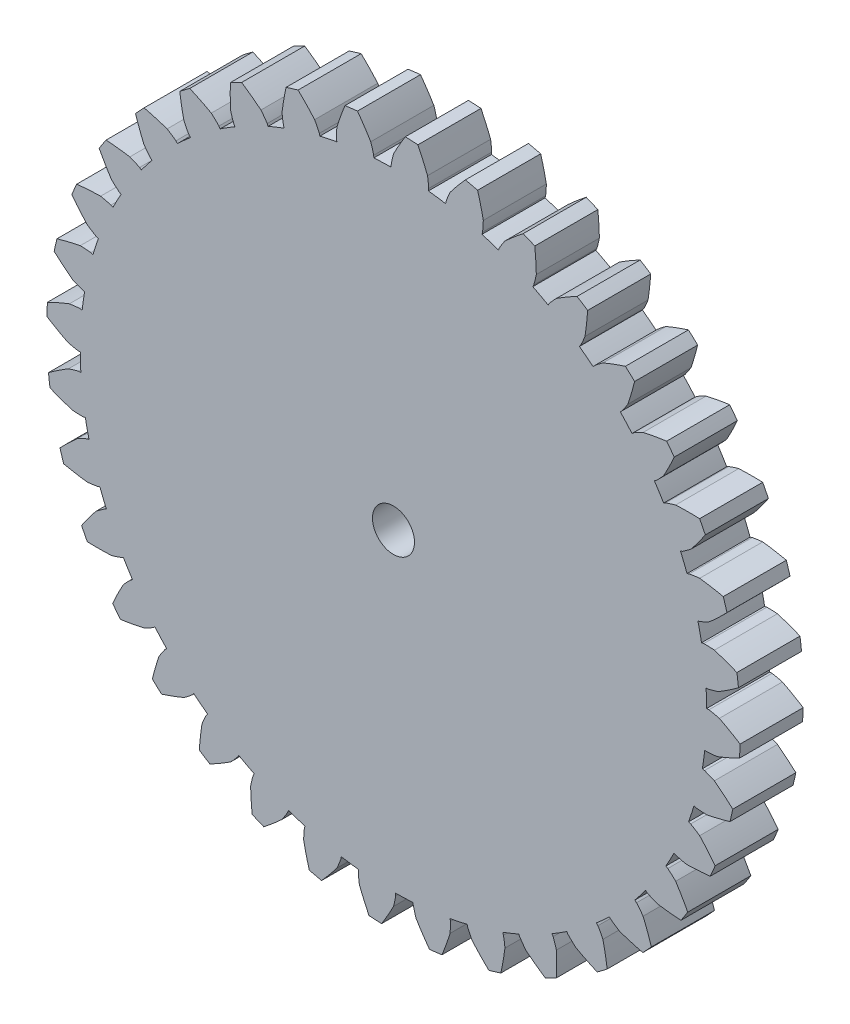
SolidWorks part; units mm, degrees
ref_plane "Front Plane" through (0, 0, 0) normal (0, 0, 1) x (1, 0, 0)
ref_plane "Top Plane" through (0, 0, 0) normal (0, 1, 0) x (1, 0, 0)
ref_plane "Right Plane" through (0, 0, 0) normal (1, 0, 0) x (0, 0, -1)
sketch "Sketch1" plane through (0, 0, 0) normal (0, 0, 1) x (1, 0, 0)
  line L0 (0, 5.8931) -> (0, -6.7835) construction
  line L1 (-10.3696, 0) -> (9.5981, 0) construction
  line L2 (-7.5145, 29.0566) -> (0, 0) construction
  line L3 (0, 0) -> (1.707, -6.6006) construction
  line L4 (-3.7573, 14.5283) -> (0, 15.5) construction
  line L5 (0, 15.5) -> (1.6202, 15.4151) construction
  line L6 (0, 0) -> (0.8101, 15.4575) construction
  line L7 (-0.1058, 15.0059) -> (-0.1058, 14.8996)
  line L8 (1.6737, 14.9127) -> (1.6626, 14.8069)
  line L9 (2.5016, 14.7963) -> (2.4831, 14.6916)
  line L10 (4.2379, 14.3955) -> (4.2086, 14.2933)
  line L11 (5.0329, 14.1371) -> (4.9966, 14.0372)
  line L12 (6.6732, 13.4409) -> (6.6266, 13.3453)
  line L13 (7.4114, 13.0484) -> (7.3582, 12.9563)
  line L14 (8.9058, 12.0779) -> (8.8433, 11.9919)
  line L15 (9.5646, 11.5632) -> (9.4963, 11.4818)
  line L16 (10.8678, 10.3479) -> (10.7914, 10.2741)
  line L17 (11.4272, 9.7266) -> (11.3458, 9.6583)
  line L18 (12.4996, 8.3035) -> (12.4115, 8.2441)
  line L19 (12.9426, 7.5946) -> (12.8506, 7.5414)
  line L20 (13.7516, 6.0068) -> (13.6545, 5.9636)
  line L21 (14.0648, 5.2317) -> (13.9649, 5.1954)
  line L22 (14.5858, 3.5276) -> (14.4826, 3.5019)
  line L23 (14.7596, 2.7099) -> (14.6549, 2.6915)
  line L24 (14.9767, 0.9413) -> (14.8707, 0.9338)
  line L25 (15.0059, 0.1058) -> (14.8996, 0.1058)
  line L26 (14.9127, -1.6737) -> (14.8069, -1.6626)
  line L27 (14.7963, -2.5016) -> (14.6916, -2.4831)
  line L28 (14.3955, -4.2379) -> (14.2933, -4.2086)
  line L29 (14.1371, -5.0329) -> (14.0372, -4.9966)
  line L30 (13.4409, -6.6732) -> (13.3453, -6.6266)
  line L31 (13.0484, -7.4114) -> (12.9563, -7.3582)
  line L32 (12.0779, -8.9058) -> (11.9919, -8.8433)
  line L33 (11.5632, -9.5646) -> (11.4818, -9.4963)
  line L34 (10.3479, -10.8678) -> (10.2741, -10.7914)
  line L35 (9.7266, -11.4272) -> (9.6583, -11.3458)
  line L36 (8.3035, -12.4996) -> (8.2441, -12.4115)
  line L37 (7.5946, -12.9426) -> (7.5414, -12.8506)
  line L38 (6.0068, -13.7516) -> (5.9636, -13.6545)
  line L39 (5.2317, -14.0648) -> (5.1954, -13.9649)
  line L40 (3.5276, -14.5858) -> (3.5019, -14.4826)
  line L41 (2.7099, -14.7596) -> (2.6915, -14.6549)
  line L42 (0.9413, -14.9767) -> (0.9338, -14.8707)
  line L43 (0.1058, -15.0059) -> (0.1058, -14.8996)
  line L44 (-1.6737, -14.9127) -> (-1.6626, -14.8069)
  line L45 (-2.5016, -14.7963) -> (-2.4831, -14.6916)
  line L46 (-4.2379, -14.3955) -> (-4.2086, -14.2933)
  line L47 (-5.0329, -14.1371) -> (-4.9966, -14.0372)
  line L48 (-6.6732, -13.4409) -> (-6.6266, -13.3453)
  line L49 (-7.4114, -13.0484) -> (-7.3582, -12.9563)
  line L50 (-8.9058, -12.0779) -> (-8.8433, -11.9919)
  line L51 (-9.5646, -11.5632) -> (-9.4963, -11.4818)
  line L52 (-10.8678, -10.3479) -> (-10.7914, -10.2741)
  line L53 (-11.4272, -9.7266) -> (-11.3458, -9.6583)
  line L54 (-12.4996, -8.3035) -> (-12.4115, -8.2441)
  line L55 (-12.9426, -7.5946) -> (-12.8506, -7.5414)
  line L56 (-13.7516, -6.0068) -> (-13.6545, -5.9636)
  line L57 (-14.0648, -5.2317) -> (-13.9649, -5.1954)
  line L58 (-14.5858, -3.5276) -> (-14.4826, -3.5019)
  line L59 (-14.7596, -2.7099) -> (-14.6549, -2.6915)
  line L60 (-14.9767, -0.9413) -> (-14.8707, -0.9338)
  line L61 (-15.0059, -0.1058) -> (-14.8996, -0.1058)
  line L62 (-14.9127, 1.6737) -> (-14.8069, 1.6626)
  line L63 (-14.7963, 2.5016) -> (-14.6916, 2.4831)
  line L64 (-14.3955, 4.2379) -> (-14.2933, 4.2086)
  line L65 (-14.1371, 5.0329) -> (-14.0372, 4.9966)
  line L66 (-13.4409, 6.6732) -> (-13.3453, 6.6266)
  line L67 (-13.0484, 7.4114) -> (-12.9563, 7.3582)
  line L68 (-12.0779, 8.9058) -> (-11.9919, 8.8433)
  line L69 (-11.5632, 9.5646) -> (-11.4818, 9.4963)
  line L70 (-10.3479, 10.8678) -> (-10.2741, 10.7914)
  line L71 (-9.7266, 11.4272) -> (-9.6583, 11.3458)
  line L72 (-8.3035, 12.4996) -> (-8.2441, 12.4115)
  line L73 (-7.5946, 12.9426) -> (-7.5414, 12.8506)
  line L74 (-6.0068, 13.7516) -> (-5.9636, 13.6545)
  line L75 (-5.2317, 14.0648) -> (-5.1954, 13.9649)
  line L76 (-3.5276, 14.5858) -> (-3.5019, 14.4826)
  line L77 (-2.7099, 14.7596) -> (-2.6915, 14.6549)
  line L78 (-0.9413, 14.9767) -> (-0.9338, 14.8707)
  circle A0 centre (0, 0) radius 15.5 construction
  arc A1 (-0.1058, 14.8996) -> (-0.9338, 14.8707) centre (0, 0) ccw
  arc A2 (1.1622, 16.459) -> (0.5646, 16.4903) centre (0, 0) ccw
  circle A3 centre (0, 0) radius 15.0063 construction
  arc A4 (0, 15.5) -> (0.5646, 16.4903) centre (11.5649, 9.5625) cw
  arc A5 (0, 15.5) -> (-0.1058, 15.0059) centre (4.8301, 14.2077) ccw
  arc A6 (1.6202, 15.4151) -> (1.1622, 16.459) centre (-10.502, 10.719) ccw
  arc A7 (1.6202, 15.4151) -> (1.6737, 14.9127) centre (-3.3185, 14.6348) cw
  arc A8 (0, 16.5) -> (16.5, 0) centre (0, 0) ccw construction
  arc A9 (2.6915, 15.2645) -> (2.5016, 14.7963) centre (7.2239, 13.1531) ccw
  arc A10 (2.6915, 15.2645) -> (3.4196, 16.1418) centre (13.0497, 7.409) cw
  arc A11 (4.0026, 16.0072) -> (3.4196, 16.1418) centre (0, 0) ccw
  arc A12 (4.2724, 14.8996) -> (4.0026, 16.0072) centre (-8.4811, 12.3798) ccw
  arc A13 (4.2724, 14.8996) -> (4.2379, 14.3955) centre (-0.7268, 14.9887) cw
  arc A14 (5.3013, 14.5652) -> (5.0329, 14.1371) centre (9.3981, 11.6989) ccw
  arc A15 (5.3013, 14.5652) -> (6.1706, 15.3027) centre (14.138, 5.0304) cw
  arc A16 (6.7214, 15.0689) -> (6.1706, 15.3027) centre (0, 0) ccw
  arc A17 (6.7948, 13.9313) -> (6.7214, 15.0689) centre (-6.2025, 13.6645) ccw
  arc A18 (6.7948, 13.9313) -> (6.6732, 13.4409) centre (1.887, 14.8872) cw
  arc A19 (7.75, 13.4234) -> (7.4114, 13.0484) centre (11.2868, 9.8892) ccw
  arc A20 (7.75, 13.4234) -> (8.7342, 13.9987) centre (14.7968, 2.499) cw
  arc A21 (9.236, 13.6728) -> (8.7342, 13.9987) centre (0, 0) ccw
  arc A22 (9.1107, 12.5398) -> (9.236, 13.6728) centre (-3.7355, 14.5339) ccw
  arc A23 (9.1107, 12.5398) -> (8.9058, 12.0779) centre (4.4434, 14.3333) cw
  arc A24 (9.9632, 11.8737) -> (9.5646, 11.5632) centre (12.8326, 7.779) ccw
  arc A25 (9.9632, 11.8737) -> (11.0323, 12.2694) centre (15.0059, -0.1084) cw
  arc A26 (11.4699, 11.8613) -> (11.0323, 12.2694) centre (0, 0) ccw
  arc A27 (11.1498, 10.7672) -> (11.4699, 11.8613) centre (-1.1549, 14.9618) ccw
  arc A28 (11.1498, 10.7672) -> (10.8678, 10.3479) centre (6.8649, 13.344) cw
  arc A29 (11.8737, 9.9632) -> (11.4272, 9.7266) centre (13.9885, 5.4325) ccw
  arc A30 (11.8737, 9.9632) -> (12.9953, 10.1673) centre (14.7591, -2.7125) cw
  arc A31 (13.3554, 9.6894) -> (12.9953, 10.1673) centre (0, 0) ccw
  arc A32 (12.8501, 8.6675) -> (13.3554, 9.6894) centre (1.4607, 14.935) ccw
  arc A33 (12.8501, 8.6675) -> (12.4996, 8.3035) centre (9.0778, 11.9492) cw
  arc A34 (13.4234, 7.75) -> (12.9426, 7.5946) centre (14.7193, 2.9209) ccw
  arc A35 (13.4234, 7.75) -> (14.5634, 7.7562) centre (14.0638, -5.2342) cw
  arc A36 (14.835, 7.223) -> (14.5634, 7.7562) centre (0, 0) ccw
  arc A37 (14.16, 6.3044) -> (14.835, 7.223) centre (4.032, 14.4545) ccw
  arc A38 (14.16, 6.3044) -> (13.7516, 6.0068) centre (11.0148, 10.1913) cw
  arc A39 (14.5652, 5.3013) -> (14.0648, 5.2317) centre (15.0029, 0.3205) ccw
  arc A40 (14.5652, 5.3013) -> (15.689, 5.1094) centre (12.9413, -7.5969) cw
  arc A41 (15.8639, 4.5372) -> (15.689, 5.1094) centre (0, 0) ccw
  arc A42 (15.0396, 3.7498) -> (15.8639, 4.5372) centre (6.4807, 13.5347) ccw
  arc A43 (15.0396, 3.7498) -> (14.5858, 3.5276) centre (12.6172, 8.1238) cw
  arc A44 (15.2645, 2.6915) -> (14.7596, 2.7099) centre (14.8306, -2.2896) ccw
  arc A45 (15.2645, 2.6915) -> (16.3379, 2.3075) centre (11.4255, -9.7287) cw
  arc A46 (16.4108, 1.7136) -> (16.3379, 2.3075) centre (0, 0) ccw
  arc A47 (15.4622, 1.0812) -> (16.4108, 1.7136) centre (8.7325, 12.2038) ccw
  arc A48 (15.4622, 1.0812) -> (14.9767, 0.9413) centre (13.8362, 5.8094) cw
  arc A49 (15.5, 0) -> (15.0059, 0.1058) centre (14.2077, -4.8301) ccw
  arc A50 (15.5, 0) -> (16.4903, -0.5646) centre (9.5625, -11.5649) cw
  arc A51 (16.459, -1.1622) -> (16.4903, -0.5646) centre (0, 0) ccw
  arc A52 (15.4151, -1.6202) -> (16.459, -1.1622) centre (10.719, 10.502) ccw
  arc A53 (15.4151, -1.6202) -> (14.9127, -1.6737) centre (14.6348, 3.3185) cw
  arc A54 (15.2645, -2.6915) -> (14.7963, -2.5016) centre (13.1531, -7.2239) ccw
  arc A55 (15.2645, -2.6915) -> (16.1418, -3.4196) centre (7.409, -13.0497) cw
  arc A56 (16.0072, -4.0026) -> (16.1418, -3.4196) centre (0, 0) ccw
  arc A57 (14.8996, -4.2724) -> (16.0072, -4.0026) centre (12.3798, 8.4811) ccw
  arc A58 (14.8996, -4.2724) -> (14.3955, -4.2379) centre (14.9887, 0.7268) cw
  arc A59 (14.5652, -5.3013) -> (14.1371, -5.0329) centre (11.6989, -9.3981) ccw
  arc A60 (14.5652, -5.3013) -> (15.3027, -6.1706) centre (5.0304, -14.138) cw
  arc A61 (15.0689, -6.7214) -> (15.3027, -6.1706) centre (0, 0) ccw
  arc A62 (13.9313, -6.7948) -> (15.0689, -6.7214) centre (13.6645, 6.2025) ccw
  arc A63 (13.9313, -6.7948) -> (13.4409, -6.6732) centre (14.8872, -1.887) cw
  arc A64 (14.0372, -4.9966) -> (14.2933, -4.2086) centre (0, 0) ccw
  arc A65 (14.6916, -2.4831) -> (14.8069, -1.6626) centre (0, 0) ccw
  arc A66 (14.8996, 0.1058) -> (14.8707, 0.9338) centre (0, 0) ccw
  arc A67 (14.6549, 2.6915) -> (14.4826, 3.5019) centre (0, 0) ccw
  arc A68 (13.9649, 5.1954) -> (13.6545, 5.9636) centre (0, 0) ccw
  arc A69 (12.8506, 7.5414) -> (12.4115, 8.2441) centre (0, 0) ccw
  arc A70 (11.3458, 9.6583) -> (10.7914, 10.2741) centre (0, 0) ccw
  arc A71 (9.4963, 11.4818) -> (8.8433, 11.9919) centre (0, 0) ccw
  arc A72 (7.3582, 12.9563) -> (6.6266, 13.3453) centre (0, 0) ccw
  arc A73 (4.9966, 14.0372) -> (4.2086, 14.2933) centre (0, 0) ccw
  arc A74 (2.4831, 14.6916) -> (1.6626, 14.8069) centre (0, 0) ccw
  circle A75 centre (0, 0) radius 1
  arc A76 (13.4234, -7.75) -> (13.0484, -7.4114) centre (9.8892, -11.2868) ccw
  arc A77 (13.4234, -7.75) -> (13.9987, -8.7342) centre (2.499, -14.7968) cw
  arc A78 (13.6728, -9.236) -> (13.9987, -8.7342) centre (0, 0) ccw
  arc A79 (12.5398, -9.1107) -> (13.6728, -9.236) centre (14.5339, 3.7355) ccw
  arc A80 (12.5398, -9.1107) -> (12.0779, -8.9058) centre (14.3333, -4.4434) cw
  arc A81 (11.8737, -9.9632) -> (11.5632, -9.5646) centre (7.779, -12.8326) ccw
  arc A82 (11.8737, -9.9632) -> (12.2694, -11.0323) centre (-0.1084, -15.0059) cw
  arc A83 (11.8613, -11.4699) -> (12.2694, -11.0323) centre (0, 0) ccw
  arc A84 (10.7672, -11.1498) -> (11.8613, -11.4699) centre (14.9618, 1.1549) ccw
  arc A85 (10.7672, -11.1498) -> (10.3479, -10.8678) centre (13.344, -6.8649) cw
  arc A86 (9.9632, -11.8737) -> (9.7266, -11.4272) centre (5.4325, -13.9885) ccw
  arc A87 (9.9632, -11.8737) -> (10.1673, -12.9953) centre (-2.7125, -14.7591) cw
  arc A88 (9.6894, -13.3554) -> (10.1673, -12.9953) centre (0, 0) ccw
  arc A89 (8.6675, -12.8501) -> (9.6894, -13.3554) centre (14.935, -1.4607) ccw
  arc A90 (8.6675, -12.8501) -> (8.3035, -12.4996) centre (11.9492, -9.0778) cw
  arc A91 (7.75, -13.4234) -> (7.5946, -12.9426) centre (2.9209, -14.7193) ccw
  arc A92 (7.75, -13.4234) -> (7.7562, -14.5634) centre (-5.2342, -14.0638) cw
  arc A93 (7.223, -14.835) -> (7.7562, -14.5634) centre (0, 0) ccw
  arc A94 (6.3044, -14.16) -> (7.223, -14.835) centre (14.4545, -4.032) ccw
  arc A95 (6.3044, -14.16) -> (6.0068, -13.7516) centre (10.1913, -11.0148) cw
  arc A96 (5.3013, -14.5652) -> (5.2317, -14.0648) centre (0.3205, -15.0029) ccw
  arc A97 (5.3013, -14.5652) -> (5.1094, -15.689) centre (-7.5969, -12.9413) cw
  arc A98 (4.5372, -15.8639) -> (5.1094, -15.689) centre (0, 0) ccw
  arc A99 (3.7498, -15.0396) -> (4.5372, -15.8639) centre (13.5347, -6.4807) ccw
  arc A100 (3.7498, -15.0396) -> (3.5276, -14.5858) centre (8.1238, -12.6172) cw
  arc A101 (2.6915, -15.2645) -> (2.7099, -14.7596) centre (-2.2896, -14.8306) ccw
  arc A102 (2.6915, -15.2645) -> (2.3075, -16.3379) centre (-9.7287, -11.4255) cw
  arc A103 (1.7136, -16.4108) -> (2.3075, -16.3379) centre (0, 0) ccw
  arc A104 (1.0812, -15.4622) -> (1.7136, -16.4108) centre (12.2038, -8.7325) ccw
  arc A105 (1.0812, -15.4622) -> (0.9413, -14.9767) centre (5.8094, -13.8362) cw
  arc A106 (0, -15.5) -> (0.1058, -15.0059) centre (-4.8301, -14.2077) ccw
  arc A107 (0, -15.5) -> (-0.5646, -16.4903) centre (-11.5649, -9.5625) cw
  arc A108 (-1.1622, -16.459) -> (-0.5646, -16.4903) centre (0, 0) ccw
  arc A109 (-1.6202, -15.4151) -> (-1.1622, -16.459) centre (10.502, -10.719) ccw
  arc A110 (-1.6202, -15.4151) -> (-1.6737, -14.9127) centre (3.3185, -14.6348) cw
  arc A111 (-2.6915, -15.2645) -> (-2.5016, -14.7963) centre (-7.2239, -13.1531) ccw
  arc A112 (-2.6915, -15.2645) -> (-3.4196, -16.1418) centre (-13.0497, -7.409) cw
  arc A113 (-4.0026, -16.0072) -> (-3.4196, -16.1418) centre (0, 0) ccw
  arc A114 (-4.2724, -14.8996) -> (-4.0026, -16.0072) centre (8.4811, -12.3798) ccw
  arc A115 (-4.2724, -14.8996) -> (-4.2379, -14.3955) centre (0.7268, -14.9887) cw
  arc A116 (-5.3013, -14.5652) -> (-5.0329, -14.1371) centre (-9.3981, -11.6989) ccw
  arc A117 (-5.3013, -14.5652) -> (-6.1706, -15.3027) centre (-14.138, -5.0304) cw
  arc A118 (-6.7214, -15.0689) -> (-6.1706, -15.3027) centre (0, 0) ccw
  arc A119 (-6.7948, -13.9313) -> (-6.7214, -15.0689) centre (6.2025, -13.6645) ccw
  arc A120 (-6.7948, -13.9313) -> (-6.6732, -13.4409) centre (-1.887, -14.8872) cw
  arc A121 (-7.75, -13.4234) -> (-7.4114, -13.0484) centre (-11.2868, -9.8892) ccw
  arc A122 (-7.75, -13.4234) -> (-8.7342, -13.9987) centre (-14.7968, -2.499) cw
  arc A123 (-9.236, -13.6728) -> (-8.7342, -13.9987) centre (0, 0) ccw
  arc A124 (-9.1107, -12.5398) -> (-9.236, -13.6728) centre (3.7355, -14.5339) ccw
  arc A125 (-9.1107, -12.5398) -> (-8.9058, -12.0779) centre (-4.4434, -14.3333) cw
  arc A126 (-9.9632, -11.8737) -> (-9.5646, -11.5632) centre (-12.8326, -7.779) ccw
  arc A127 (-9.9632, -11.8737) -> (-11.0323, -12.2694) centre (-15.0059, 0.1084) cw
  arc A128 (-11.4699, -11.8613) -> (-11.0323, -12.2694) centre (0, 0) ccw
  arc A129 (-11.1498, -10.7672) -> (-11.4699, -11.8613) centre (1.1549, -14.9618) ccw
  arc A130 (-11.1498, -10.7672) -> (-10.8678, -10.3479) centre (-6.8649, -13.344) cw
  arc A131 (-11.8737, -9.9632) -> (-11.4272, -9.7266) centre (-13.9885, -5.4325) ccw
  arc A132 (-11.8737, -9.9632) -> (-12.9953, -10.1673) centre (-14.7591, 2.7125) cw
  arc A133 (-13.3554, -9.6894) -> (-12.9953, -10.1673) centre (0, 0) ccw
  arc A134 (-12.8501, -8.6675) -> (-13.3554, -9.6894) centre (-1.4607, -14.935) ccw
  arc A135 (-12.8501, -8.6675) -> (-12.4996, -8.3035) centre (-9.0778, -11.9492) cw
  arc A136 (-13.4234, -7.75) -> (-12.9426, -7.5946) centre (-14.7193, -2.9209) ccw
  arc A137 (-13.4234, -7.75) -> (-14.5634, -7.7562) centre (-14.0638, 5.2342) cw
  arc A138 (-14.835, -7.223) -> (-14.5634, -7.7562) centre (0, 0) ccw
  arc A139 (-14.16, -6.3044) -> (-14.835, -7.223) centre (-4.032, -14.4545) ccw
  arc A140 (-14.16, -6.3044) -> (-13.7516, -6.0068) centre (-11.0148, -10.1913) cw
  arc A141 (-14.5652, -5.3013) -> (-14.0648, -5.2317) centre (-15.0029, -0.3205) ccw
  arc A142 (-14.5652, -5.3013) -> (-15.689, -5.1094) centre (-12.9413, 7.5969) cw
  arc A143 (-15.8639, -4.5372) -> (-15.689, -5.1094) centre (0, 0) ccw
  arc A144 (-15.0396, -3.7498) -> (-15.8639, -4.5372) centre (-6.4807, -13.5347) ccw
  arc A145 (-15.0396, -3.7498) -> (-14.5858, -3.5276) centre (-12.6172, -8.1238) cw
  arc A146 (-15.2645, -2.6915) -> (-14.7596, -2.7099) centre (-14.8306, 2.2896) ccw
  arc A147 (-15.2645, -2.6915) -> (-16.3379, -2.3075) centre (-11.4255, 9.7287) cw
  arc A148 (-16.4108, -1.7136) -> (-16.3379, -2.3075) centre (0, 0) ccw
  arc A149 (-15.4622, -1.0812) -> (-16.4108, -1.7136) centre (-8.7325, -12.2038) ccw
  arc A150 (-15.4622, -1.0812) -> (-14.9767, -0.9413) centre (-13.8362, -5.8094) cw
  arc A151 (-15.5, 0) -> (-15.0059, -0.1058) centre (-14.2077, 4.8301) ccw
  arc A152 (-15.5, 0) -> (-16.4903, 0.5646) centre (-9.5625, 11.5649) cw
  arc A153 (-16.459, 1.1622) -> (-16.4903, 0.5646) centre (0, 0) ccw
  arc A154 (-15.4151, 1.6202) -> (-16.459, 1.1622) centre (-10.719, -10.502) ccw
  arc A155 (-15.4151, 1.6202) -> (-14.9127, 1.6737) centre (-14.6348, -3.3185) cw
  arc A156 (-15.2645, 2.6915) -> (-14.7963, 2.5016) centre (-13.1531, 7.2239) ccw
  arc A157 (-15.2645, 2.6915) -> (-16.1418, 3.4196) centre (-7.409, 13.0497) cw
  arc A158 (-16.0072, 4.0026) -> (-16.1418, 3.4196) centre (0, 0) ccw
  arc A159 (-14.8996, 4.2724) -> (-16.0072, 4.0026) centre (-12.3798, -8.4811) ccw
  arc A160 (-14.8996, 4.2724) -> (-14.3955, 4.2379) centre (-14.9887, -0.7268) cw
  arc A161 (-14.5652, 5.3013) -> (-14.1371, 5.0329) centre (-11.6989, 9.3981) ccw
  arc A162 (-14.5652, 5.3013) -> (-15.3027, 6.1706) centre (-5.0304, 14.138) cw
  arc A163 (-15.0689, 6.7214) -> (-15.3027, 6.1706) centre (0, 0) ccw
  arc A164 (-13.9313, 6.7948) -> (-15.0689, 6.7214) centre (-13.6645, -6.2025) ccw
  arc A165 (-13.9313, 6.7948) -> (-13.4409, 6.6732) centre (-14.8872, 1.887) cw
  arc A166 (-13.4234, 7.75) -> (-13.0484, 7.4114) centre (-9.8892, 11.2868) ccw
  arc A167 (-13.4234, 7.75) -> (-13.9987, 8.7342) centre (-2.499, 14.7968) cw
  arc A168 (-13.6728, 9.236) -> (-13.9987, 8.7342) centre (0, 0) ccw
  arc A169 (-12.5398, 9.1107) -> (-13.6728, 9.236) centre (-14.5339, -3.7355) ccw
  arc A170 (-12.5398, 9.1107) -> (-12.0779, 8.9058) centre (-14.3333, 4.4434) cw
  arc A171 (-11.8737, 9.9632) -> (-11.5632, 9.5646) centre (-7.779, 12.8326) ccw
  arc A172 (-11.8737, 9.9632) -> (-12.2694, 11.0323) centre (0.1084, 15.0059) cw
  arc A173 (-11.8613, 11.4699) -> (-12.2694, 11.0323) centre (0, 0) ccw
  arc A174 (-10.7672, 11.1498) -> (-11.8613, 11.4699) centre (-14.9618, -1.1549) ccw
  arc A175 (-10.7672, 11.1498) -> (-10.3479, 10.8678) centre (-13.344, 6.8649) cw
  arc A176 (-9.9632, 11.8737) -> (-9.7266, 11.4272) centre (-5.4325, 13.9885) ccw
  arc A177 (-9.9632, 11.8737) -> (-10.1673, 12.9953) centre (2.7125, 14.7591) cw
  arc A178 (-9.6894, 13.3554) -> (-10.1673, 12.9953) centre (0, 0) ccw
  arc A179 (-8.6675, 12.8501) -> (-9.6894, 13.3554) centre (-14.935, 1.4607) ccw
  arc A180 (-8.6675, 12.8501) -> (-8.3035, 12.4996) centre (-11.9492, 9.0778) cw
  arc A181 (-7.75, 13.4234) -> (-7.5946, 12.9426) centre (-2.9209, 14.7193) ccw
  arc A182 (-7.75, 13.4234) -> (-7.7562, 14.5634) centre (5.2342, 14.0638) cw
  arc A183 (-7.223, 14.835) -> (-7.7562, 14.5634) centre (0, 0) ccw
  arc A184 (-6.3044, 14.16) -> (-7.223, 14.835) centre (-14.4545, 4.032) ccw
  arc A185 (-6.3044, 14.16) -> (-6.0068, 13.7516) centre (-10.1913, 11.0148) cw
  arc A186 (-5.3013, 14.5652) -> (-5.2317, 14.0648) centre (-0.3205, 15.0029) ccw
  arc A187 (-5.3013, 14.5652) -> (-5.1094, 15.689) centre (7.5969, 12.9413) cw
  arc A188 (-4.5372, 15.8639) -> (-5.1094, 15.689) centre (0, 0) ccw
  arc A189 (-3.7498, 15.0396) -> (-4.5372, 15.8639) centre (-13.5347, 6.4807) ccw
  arc A190 (-3.7498, 15.0396) -> (-3.5276, 14.5858) centre (-8.1238, 12.6172) cw
  arc A191 (-2.6915, 15.2645) -> (-2.7099, 14.7596) centre (2.2896, 14.8306) ccw
  arc A192 (-2.6915, 15.2645) -> (-2.3075, 16.3379) centre (9.7287, 11.4255) cw
  arc A193 (-1.7136, 16.4108) -> (-2.3075, 16.3379) centre (0, 0) ccw
  arc A194 (-1.0812, 15.4622) -> (-1.7136, 16.4108) centre (-12.2038, 8.7325) ccw
  arc A195 (-1.0812, 15.4622) -> (-0.9413, 14.9767) centre (-5.8094, 13.8362) cw
  arc A196 (-2.6915, 14.6549) -> (-3.5019, 14.4826) centre (0, 0) ccw
  arc A197 (-5.1954, 13.9649) -> (-5.9636, 13.6545) centre (0, 0) ccw
  arc A198 (-9.6583, 11.3458) -> (-10.2741, 10.7914) centre (0, 0) ccw
  arc A199 (-7.5414, 12.8506) -> (-8.2441, 12.4115) centre (0, 0) ccw
  arc A200 (-11.4818, 9.4963) -> (-11.9919, 8.8433) centre (0, 0) ccw
  arc A201 (-12.9563, 7.3582) -> (-13.3453, 6.6266) centre (0, 0) ccw
  arc A202 (-14.0372, 4.9966) -> (-14.2933, 4.2086) centre (0, 0) ccw
  arc A203 (-13.9649, -5.1954) -> (-13.6545, -5.9636) centre (0, 0) ccw
  arc A204 (-14.6549, -2.6915) -> (-14.4826, -3.5019) centre (0, 0) ccw
  arc A205 (-14.8996, -0.1058) -> (-14.8707, -0.9338) centre (0, 0) ccw
  arc A206 (-14.6916, 2.4831) -> (-14.8069, 1.6626) centre (0, 0) ccw
  arc A207 (12.9563, -7.3582) -> (13.3453, -6.6266) centre (0, 0) ccw
  arc A208 (11.4818, -9.4963) -> (11.9919, -8.8433) centre (0, 0) ccw
  arc A209 (9.6583, -11.3458) -> (10.2741, -10.7914) centre (0, 0) ccw
  arc A210 (7.5414, -12.8506) -> (8.2441, -12.4115) centre (0, 0) ccw
  arc A211 (5.1954, -13.9649) -> (5.9636, -13.6545) centre (0, 0) ccw
  arc A212 (2.6915, -14.6549) -> (3.5019, -14.4826) centre (0, 0) ccw
  arc A213 (0.1058, -14.8996) -> (0.9338, -14.8707) centre (0, 0) ccw
  arc A214 (-2.4831, -14.6916) -> (-1.6626, -14.8069) centre (0, 0) ccw
  arc A215 (-4.9966, -14.0372) -> (-4.2086, -14.2933) centre (0, 0) ccw
  arc A216 (-7.3582, -12.9563) -> (-6.6266, -13.3453) centre (0, 0) ccw
  arc A217 (-9.4963, -11.4818) -> (-8.8433, -11.9919) centre (0, 0) ccw
  arc A218 (-11.3458, -9.6583) -> (-10.7914, -10.2741) centre (0, 0) ccw
  arc A219 (-12.8506, -7.5414) -> (-12.4115, -8.2441) centre (0, 0) ccw
  point P10 (0, 15.5)
  point P15 (1.6202, 15.4151)
  point P16 (3.2226, 15.1613)
  point P17 (4.7898, 14.7414)
  point P18 (6.3044, 14.16)
  point P19 (7.75, 13.4234)
  point P20 (9.1107, 12.5398)
  point P21 (10.3715, 11.5187)
  point P22 (11.5187, 10.3715)
  point P23 (12.5398, 9.1107)
  point P24 (13.4234, 7.75)
  point P25 (14.16, 6.3044)
  point P26 (14.7414, 4.7898)
  point P27 (15.1613, 3.2226)
  point P28 (15.4151, 1.6202)
  point P29 (15.5, 0)
  point P30 (15.4151, -1.6202)
  point P31 (15.1613, -3.2226)
  point P32 (0, 0)
  point P41 (14.7414, -4.7898)
  point P42 (14.16, -6.3044)
  point P180 (0, 0)
  point P181 (13.4234, -7.75)
  point P182 (12.5398, -9.1107)
  point P183 (11.5187, -10.3715)
  point P184 (10.3715, -11.5187)
  point P185 (9.1107, -12.5398)
  point P186 (7.75, -13.4234)
  point P187 (6.3044, -14.16)
  point P188 (4.7898, -14.7414)
  point P189 (3.2226, -15.1613)
  point P190 (1.6202, -15.4151)
  point P191 (0, -15.5)
  point P192 (-1.6202, -15.4151)
  point P193 (-3.2226, -15.1613)
  point P194 (-4.7898, -14.7414)
  point P195 (-6.3044, -14.16)
  point P196 (-7.75, -13.4234)
  point P197 (-9.1107, -12.5398)
  point P198 (-10.3715, -11.5187)
  point P199 (-11.5187, -10.3715)
  point P200 (-12.5398, -9.1107)
  point P201 (-13.4234, -7.75)
  point P202 (-14.16, -6.3044)
  point P203 (-14.7414, -4.7898)
  point P204 (-15.1613, -3.2226)
  point P205 (-15.4151, -1.6202)
  point P206 (-15.5, 0)
  point P207 (-15.4151, 1.6202)
  point P208 (-15.1613, 3.2226)
  point P209 (-14.7414, 4.7898)
  point P210 (-14.16, 6.3044)
  point P211 (-13.4234, 7.75)
  point P212 (-12.5398, 9.1107)
  point P213 (-11.5187, 10.3715)
  point P214 (-10.3715, 11.5187)
  point P215 (-9.1107, 12.5398)
  point P216 (-7.75, 13.4234)
  point P217 (-6.3044, 14.16)
  point P218 (-4.7898, 14.7414)
  point P219 (-3.2226, 15.1613)
  point P220 (-1.6202, 15.4151)
  dimension "D1" = 31
  dimension "D2" = 1
  dimension "D3" = 0.6
  dimension "D6" = 13
  dimension "D7" = 5
  dimension "D9" = 2
  dimension "D4" = 14.5
  dimension "D5" = 60
  dimension "D8" = 36
extrude "Boss-Extrude1" add sketch "Sketch1" along normal mid plane 3
